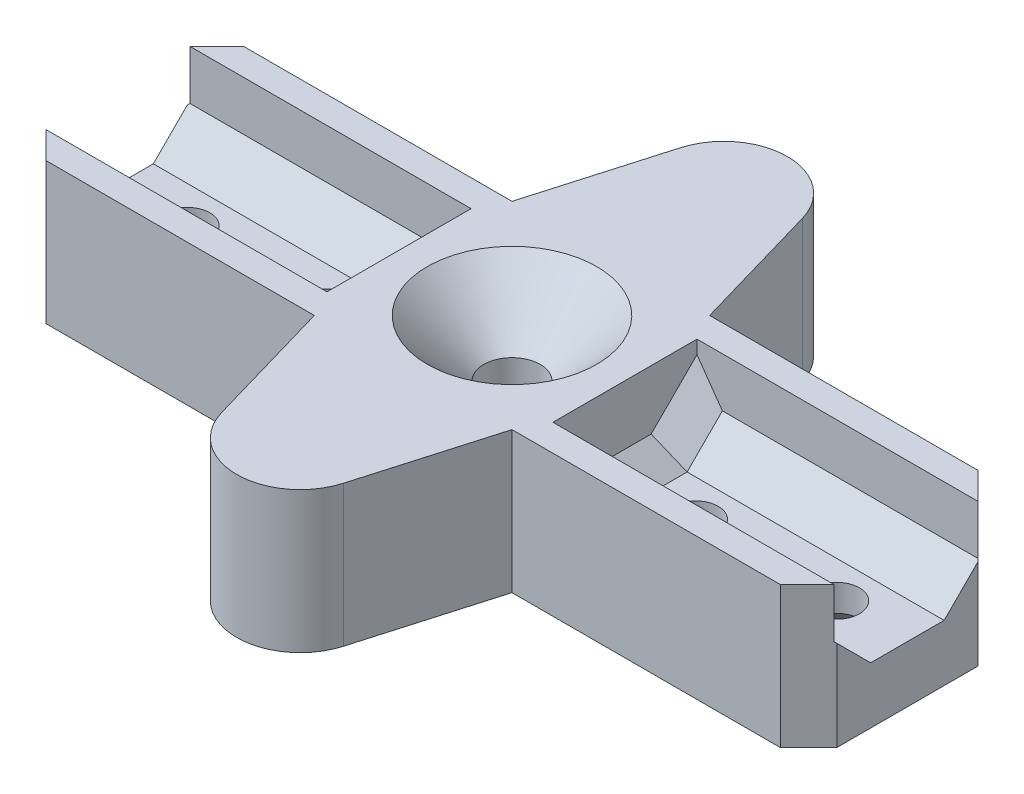
SolidWorks part; units mm, degrees
ref_plane "Plan de face" through (0, 0, 0) normal (0, 0, 1) x (1, 0, 0)
ref_plane "Plan de dessus" through (0, 0, 0) normal (0, 1, 0) x (1, 0, 0)
ref_plane "Plan de droite" through (0, 0, 0) normal (1, 0, 0) x (0, 0, -1)
sketch "Esquisse1" plane through (0, 0, 0) normal (0, 1, 0) x (1, 0, 0)
  line L0 (7, 7) -> (28, 7)
  line L1 (-28, -7) -> (-7, -7)
  line L2 (-28, -7) -> (-28, 7)
  line L3 (-28, 7) -> (-7, 7)
  line L4 (28, -7) -> (28, 7)
  line L5 (-28, -7) -> (28, 7) construction
  line L6 (-28, 7) -> (28, -7) construction
  line L7 (7, -7) -> (28, -7)
  line L8 (-7, 7) -> (-4.3226, 16.251)
  line L9 (7, 7) -> (4.3226, 16.251)
  line L10 (-7, -7) -> (-4.3226, -16.251)
  line L11 (7, -7) -> (4.3226, -16.251)
  circle A0 centre (0, 0) radius 2
  arc A2 (4.3226, 16.251) -> (-4.3226, 16.251) centre (0, 15) ccw
  arc A3 (-4.3226, -16.251) -> (4.3226, -16.251) centre (0, -15) ccw
  dimension "D1" = 14
  dimension "D9" = 9
  dimension "D10" = 9
  dimension "D11" = 4
  dimension "D2" = 14
  dimension "D3" = 56
  dimension "D4" = 14
  dimension "D5" = 7
  dimension "D6" = 7
  dimension "D7" = 15
  dimension "D8" = 15
extrude "Boss.-Extru.1" add sketch "Esquisse1" along normal blind 10
sketch "Esquisse2" plane through (-28, 0, 0) normal (-1, 0, 0) x (0, 0, 1)
  line L0 (-7, 10) -> (7, 10) construction
  line L1 (-5.1, 10) -> (5.1, 10)
  line L2 (-5.1, 10) -> (-5.1, 4)
  line L3 (-5.1, 4) -> (5.1, 4)
  line L4 (5.1, 10) -> (5.1, 4)
  line L5 (-7, 0) -> (7, 0) construction
  point P6 (0, 0)
  dimension "D1" = 6
  dimension "D2" = 10.2
  dimension "D3" = 5.1
extrude "Enlèv. mat.-Extru.1" cut sketch "Esquisse2" against normal blind 20
chamfer "Chanfrein1" distance 2.5 angle 45 2 edges at (-18, 4, 5.1) (-18, 4, -5.1)
chamfer "Chanfrein2" distance 1.8 angle 45 3 edges at (-8, 5.25, 3.85) (-8, 4, 0) (-8, 5.25, -3.85)
mirror "Symétrie1" about plane through (0, 0, 0) normal (1, 0, 0) of "Chanfrein2", "Chanfrein1", "Enlèv. mat.-Extru.1"
sketch "Esquisse5" plane through (0, 0, 0) normal (0, -1, 0) x (1, 0, 0)
  line L0 (-32.8926, 0) -> (36.0103, 0) construction
  line L1 (28, 7) -> (28, -7) construction
  line L2 (-28, -7) -> (-28, 7) construction
  circle A0 centre (-23, 0) radius 1.6
  circle A1 centre (-13, 0) radius 1.6
  circle A2 centre (13, 0) radius 1.6
  circle A3 centre (23, 0) radius 1.6
  dimension "D1" = 3.2
  dimension "D2" = 3.2
  dimension "D3" = 3.2
  dimension "D4" = 3.2
  dimension "D5" = 5
  dimension "D6" = 10
  dimension "D7" = 10
  dimension "D8" = 5
extrude "Enlèv. mat.-Extru.4" cut sketch "Esquisse5" against normal blind 7
chamfer "Chanfrein4" distance 2.1 angle 45 4 edges at (23, 0, -1.6) (13, 0, -1.6) (-23, 0, -1.6) (-13, 0, -1.6)
chamfer "Chanfrein5" distance 2 angle 45 4 edges at (28, 5, -7) (28, 5, 7) (-28, 5, -7) (-28, 5, 7)
sketch "Esquisse6" plane through (0, 0, 0) normal (0, -1, 0) x (1, 0, 0)
  line L0 (-3.9799, -0.4) -> (-2.4875, -15.25)
  line L1 (3.9799, -0.4) -> (2.4875, -15.25)
  line L2 (-3.9799, 0.4) -> (-2.4875, 15.25)
  line L3 (2.4875, 15.25) -> (3.9799, 0.4)
  arc A0 (-3.9799, 0.4) -> (-3.9799, -0.4) centre (0, 0) ccw
  arc A1 (2.4875, 15.25) -> (-2.4875, 15.25) centre (0, 15) ccw
  arc A2 (-2.4875, -15.25) -> (2.4875, -15.25) centre (0, -15) ccw
  arc A3 (3.9799, -0.4) -> (3.9799, 0.4) centre (0, 0) ccw
  dimension "D3" = 5
  dimension "D4" = 5
  dimension "D5" = 8
  dimension "D1" = 15
  dimension "D2" = 30
extrude "Enlèv. mat.-Extru.5" cut sketch "Esquisse6" against normal blind 4
chamfer "Chanfrein6" distance 4 angle 45 1 edges at (0, 10, 2)
